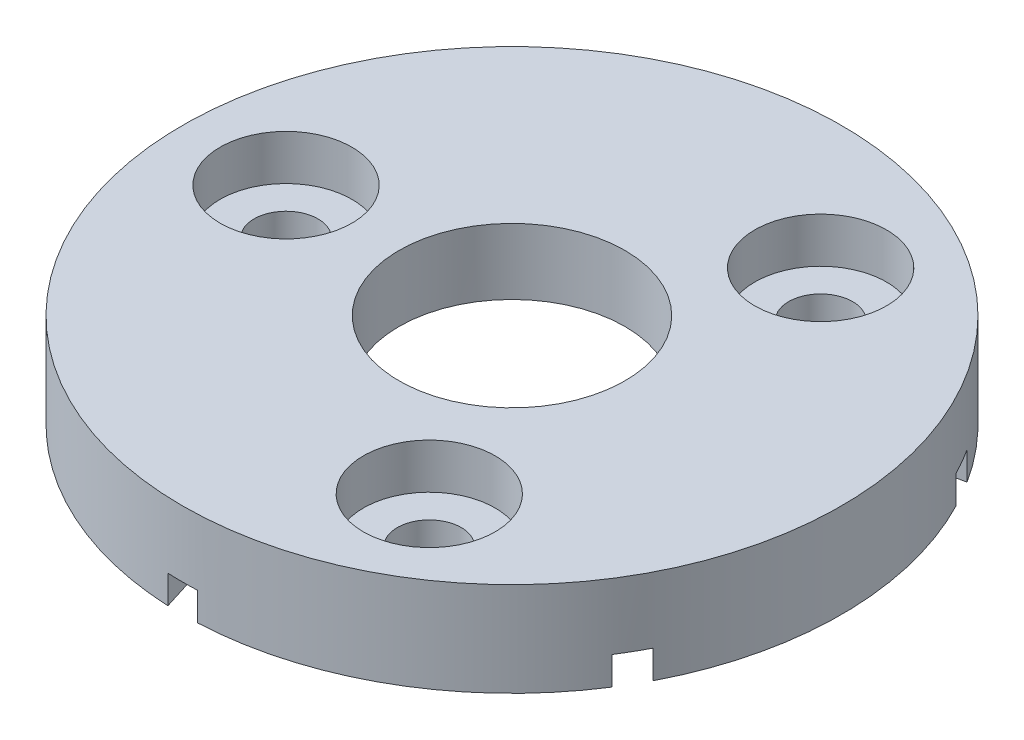
SolidWorks part; units mm, degrees
ref_plane "Front Plane" through (0, 0, 0) normal (0, 0, 1) x (1, 0, 0)
ref_plane "Top Plane" through (0, 0, 0) normal (0, 1, 0) x (1, 0, 0)
ref_plane "Right Plane" through (0, 0, 0) normal (1, 0, 0) x (0, 0, -1)
sketch "Sketch1" plane through (0, 0, 0) normal (0, 1, 0) x (1, 0, 0)
  circle A0 centre (0, 0) radius 17.5
  dimension "D1" = 35
extrude "Boss-Extrude1" add sketch "Sketch1" along normal blind 5
hole_wizard "CBORE for M3 Pan Head Screw1" positions "Sketch3" profile "Sketch2" counterbore size "M3" standard "ISO" end condition through all
sketch "Sketch3" plane through (0, 5, 0) normal (0, 1, 0) x (1, 0, 0)
  point P0 (-12, 0)
  dimension "D1" = 12
sketch "Sketch2" plane through (-12, 5, 0) normal (1, 0, 0) x (0, 0, 1)
  line L0 (0, 0) -> (0, 5)
  line L1 (0, 5) -> (1.7, 5)
  line L3 (1.7, 5) -> (1.7, 2.4)
  line L4 (1.7, 2.4) -> (3.5, 2.4)
  line L5 (3.5, 2.4) -> (3.5, 0)
  line L7 (3.5, 0) -> (0, 0)
  line L11 (0, -6.35) -> (0, 107.95) construction
  dimension "Thru Hole Dia." = 3.4
  dimension "Thru Hole Depth" = 5
  dimension "C'Bore Dia." = 7
  dimension "C'Bore Depth" = 2.4
pattern_circular "CirPattern1" count 3 over 360 about axis through (0, 0, 0) along (0, 1, 0) of "CBORE for M3 Pan Head Screw1"
hole_wizard "Ø12.0 (12) Diameter Hole1" positions "Sketch5" profile "Sketch6" hole size "Ø12.0" standard "ISO" end condition through all
sketch "Sketch5" plane through (0, 0, 0) normal (0, -1, 0) x (-1, 0, 0)
  point P0 (0, 0)
sketch "Sketch6" plane through (0, 0, 0) normal (1, 0, 0) x (0, 0, -1)
  line L0 (0, 0) -> (0, 5)
  line L1 (0, 5) -> (6, 5)
  line L2 (6, 5) -> (6, 0)
  line L5 (6, 0) -> (0, 0)
  line L11 (0, -6.35) -> (0, 107.95) construction
  dimension "Thru Hole Dia." = 12
  dimension "Thru Hole Depth" = 5
sketch "Sketch7" plane through (0, 0, 0) normal (0, -1, 0) x (1, 0, 0)
  line L0 (0, 0) -> (0, 20) construction
  line L1 (0, 20) -> (-5.7236, 1.8)
  line L2 (-5.7236, 1.8) -> (5.7236, 1.8)
  line L3 (5.7236, 1.8) -> (0, 20)
  circle A0 centre (0, 0) radius 6 construction
  dimension "D1" = 20
extrude "Cut-Extrude1" cut sketch "Sketch7" against normal blind 1.5
pattern_circular "CirPattern2" count 6 over 360 about axis through (0, 0, 0) along (0, 1, 0) of "Cut-Extrude1"
